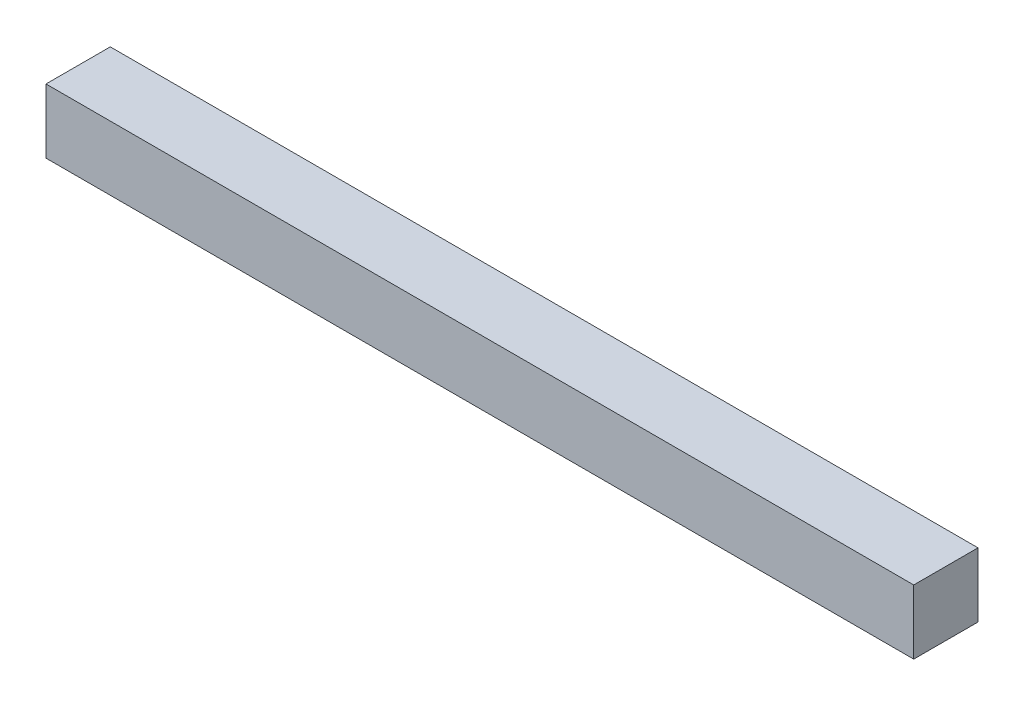
SolidWorks part; units mm, degrees
ref_plane "前视基准面" through (0, 0, 0) normal (0, 0, 1) x (1, 0, 0)
ref_plane "上视基准面" through (0, 0, 0) normal (0, 1, 0) x (1, 0, 0)
ref_plane "右视基准面" through (0, 0, 0) normal (1, 0, 0) x (0, 0, -1)
sketch "草图1" plane through (0, 0, 0) normal (1, 0, 0) x (0, 0, -1)
  line L1 (-10, -10) -> (10, -10)
  line L2 (-10, -10) -> (-10, 10)
  line L3 (-10, 10) -> (10, 10)
  line L4 (10, -10) -> (10, 10)
  line L5 (-10, -10) -> (10, 10) construction
  line L6 (-10, 10) -> (10, -10) construction
  point P0 (0, 0)
  dimension "D1" = 20
  dimension "D2" = 20
extrude "凸台-拉伸1" add sketch "草图1" along normal blind 270
